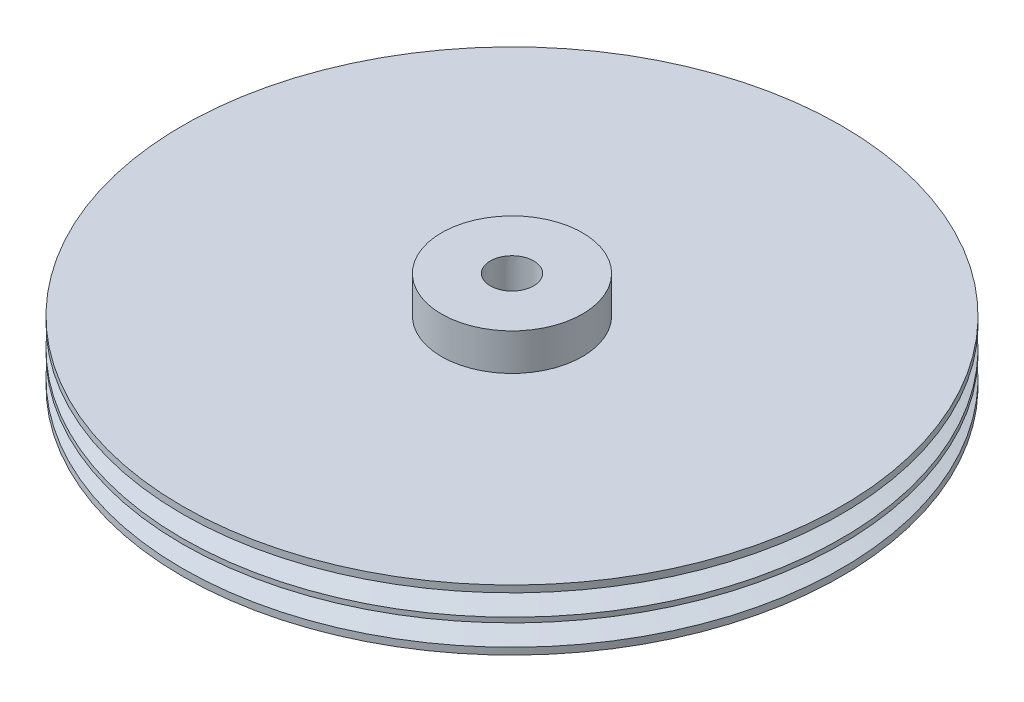
SolidWorks part; units mm, degrees
ref_plane "Front Plane" through (0, 0, 0) normal (0, 0, 1) x (1, 0, 0)
ref_plane "Top Plane" through (0, 0, 0) normal (0, 1, 0) x (1, 0, 0)
ref_plane "Right Plane" through (0, 0, 0) normal (1, 0, 0) x (0, 0, -1)
sketch "Sketch1" plane through (0, 0, 0) normal (0, 0, 1) x (1, 0, 0)
  line L0 (0, 18.7985) -> (0, 0) construction
  line L1 (10, 45) -> (10, 0)
  line L2 (10, 0) -> (152, 0)
  line L3 (152, 0) -> (152, 3.1385)
  line L4 (152, 3.1385) -> (141, 6.5016)
  line L5 (141, 6.5016) -> (141, 9.4984)
  line L6 (141, 9.4984) -> (152, 12.8615)
  line L7 (152, 12.8615) -> (152, 15.1385)
  line L8 (152, 15.1385) -> (141, 18.5016)
  line L9 (141, 18.5016) -> (141, 21.4984)
  line L10 (141, 21.4984) -> (152, 24.8615)
  line L11 (152, 24.8615) -> (152, 28)
  line L12 (152, 28) -> (32.5, 28)
  line L13 (32.5, 28) -> (32.5, 45)
  line L14 (32.5, 45) -> (10, 45)
  line L15 (150, 30.1194) -> (150, -2.7923) construction
  line L16 (152, 8) -> (0, 8) construction
  line L17 (152, 20) -> (0, 20) construction
  point P23 (141, 20)
  point P24 (141, 8)
  point P25 (150, 24.25)
  point P26 (150, 15.75)
  point P27 (150, 12.25)
  point P28 (150, 3.75)
  dimension "D1" = 20
  dimension "D2" = 34
  dimension "D3" = 300
  dimension "D4" = 9
  dimension "D5" = 8
  dimension "D6" = 12
  dimension "D7" = 2
  dimension "D8" = 8.5
  dimension "D9" = 65
  dimension "D10" = 17
revolve "Revolve1" add sketch "Sketch1" angle 360 about L0
equation "\"f_poulie_receptrice\"=8"
equation "\"D5@Sketch1\"=\"f_poulie_receptrice\""
equation "\"e_poulie_receptrice\"=12"
equation "\"D6@Sketch1\"=\"e_poulie_receptrice\""
equation "\"b_poulie_receptrice\"=2"
equation "\"D7@Sketch1\"=\"b_poulie_receptrice\""
equation "\"h_gorge_poulie_receptrice\"=9"
equation "\"D4@Sketch1\"=\"h_gorge_poulie_receptrice\""
equation "\"W_poulie_receptrice\"=8.5"
equation "\"D8@Sketch1\"=\"W_poulie_receptrice\""
